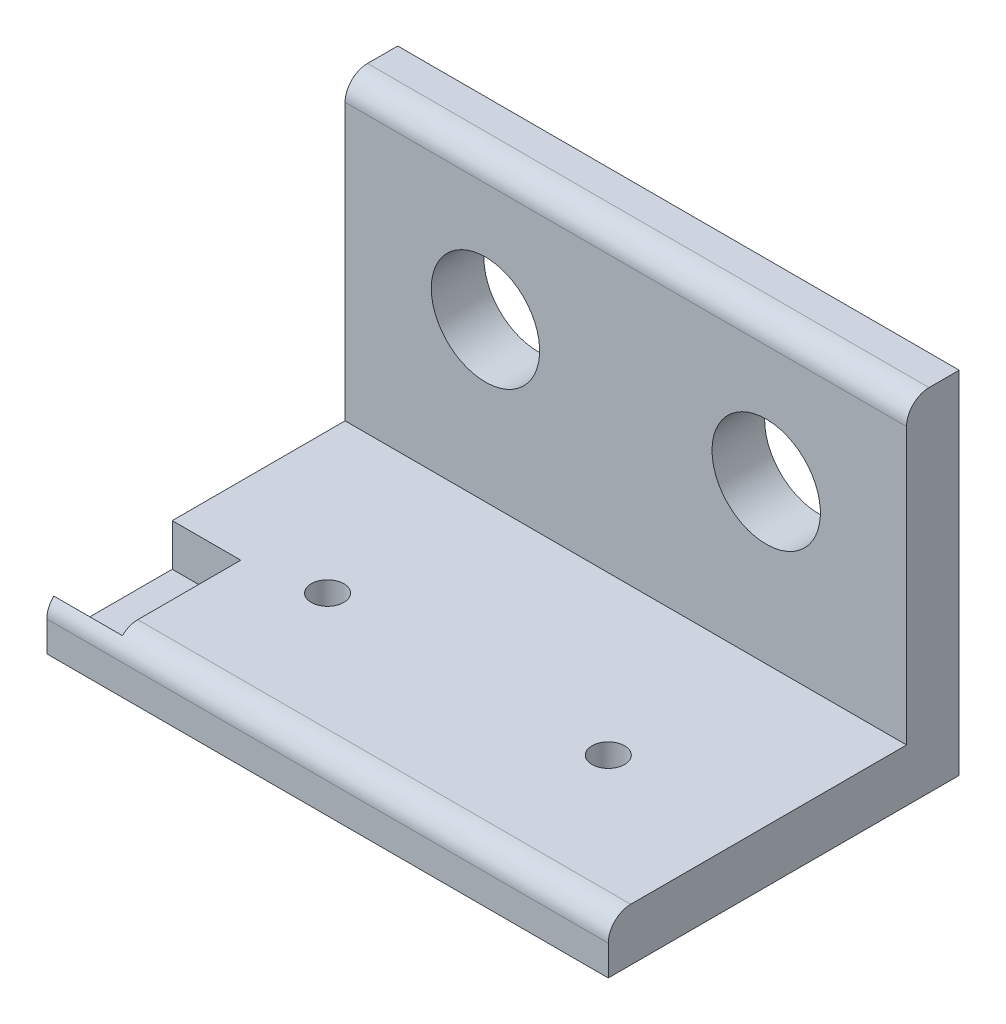
SolidWorks part; units mm, degrees
material "6061 Alloy"
ref_plane "Front" through (0, 0, 0) normal (0, 0, 1) x (1, 0, 0)
ref_plane "Top" through (0, 0, 0) normal (0, 1, 0) x (1, 0, 0)
ref_plane "Right" through (0, 0, 0) normal (1, 0, 0) x (0, 0, -1)
sketch "Sketch1" plane through (0, 0, 0) normal (0, 1, 0) x (1, 0, 0)
  line L1 (0, 0) -> (50.8, 0)
  line L2 (0, 0) -> (0, -31.75)
  line L3 (0, -31.75) -> (50.8, -31.75)
  line L4 (50.8, 0) -> (50.8, -31.75)
  dimension "D1" = 31.75
  dimension "D2" = 50.8
extrude "Base leg" add sketch "Sketch1" along normal blind 4.7625
sketch "Sketch2" plane through (0, 0, 0) normal (0, 0, 1) x (1, 0, 0)
  line L1 (0, 0) -> (50.8, 0)
  line L2 (0, 0) -> (0, 31.75)
  line L3 (0, 31.75) -> (50.8, 31.75)
  line L4 (50.8, 0) -> (50.8, 31.75)
  dimension "D1" = 31.75
  dimension "D2" = 50.8
extrude "Perpendicular leg" add sketch "Sketch2" along normal blind 4.7625
fillet "Fillet1" radius 2.032 2 edges at (25.4, 31.75, 4.7625) (25.4, 4.7625, 31.75)
hole_wizard "#32 (0.116) Diameter Hole1" positions "Sketch11" profile "Sketch12" hole size "#32" standard "ANSI Inch" end condition through all
sketch "Sketch11" plane through (0, 0, 0) normal (0, -1, 0) x (-1, 0, 0)
  line L1 (-50.8, 0) -> (-50.8, -31.75) construction
  line L5 (-50.8, 0) -> (0, 0) construction
  point P0 (-38.1, -19.05)
  point P2 (-12.7, -19.05)
  dimension "D1" = 19.05
  dimension "D2" = 25.4
  dimension "D3" = 12.7
sketch "Sketch12" plane through (38.1, 0, 19.05) normal (1, 0, 0) x (0, 0, -1)
  line L0 (0, 0) -> (0, 31.75)
  line L1 (0, 31.75) -> (1.4732, 31.75)
  line L2 (1.4732, 31.75) -> (1.4732, 0)
  line L5 (1.4732, 0) -> (0, 0)
  line L11 (0, -6.35) -> (0, 107.95) construction
  dimension "Thru Hole Dia." = 2.9464
  dimension "Thru Hole Depth" = 31.75
hole_wizard "W (0.386) Diameter Hole1" positions "Sketch13" profile "Sketch14" hole size "W" standard "ANSI Inch" end condition through all
sketch "Sketch13" plane through (0, 0, 0) normal (0, 0, -1) x (-1, 0, 0)
  line L0 (0, 0) -> (-50.8, 0) construction
  line L1 (0, 0) -> (0, 31.75) construction
  point P0 (-12.7, 19.05)
  point P2 (-38.1, 19.05)
  dimension "D1" = 19.05
  dimension "D2" = 25.4
  dimension "D3" = 12.7
sketch "Sketch14" plane through (12.7, 19.05, 0) normal (1, 0, 0) x (0, 1, 0)
  line L0 (0, 0) -> (0, 31.75)
  line L1 (0, 31.75) -> (4.9022, 31.75)
  line L2 (4.9022, 31.75) -> (4.9022, 0)
  line L5 (4.9022, 0) -> (0, 0)
  line L11 (0, -6.35) -> (0, 107.95) construction
  dimension "Thru Hole Dia." = 9.8044
  dimension "Thru Hole Depth" = 31.75
sketch "Sketch15" plane through (0, 4.7625, 0) normal (0, 1, 0) x (1, 0, 0)
  line L1 (-0.3485, -31.113) -> (6.2012, -31.113)
  line L2 (-0.3485, -31.113) -> (-0.3485, -20.3992)
  line L3 (-0.3485, -20.3992) -> (6.2012, -20.3992)
  line L4 (6.2012, -31.113) -> (6.2012, -20.3992)
extrude "Cut-Extrude2" cut sketch "Sketch15" against normal blind 3.81
